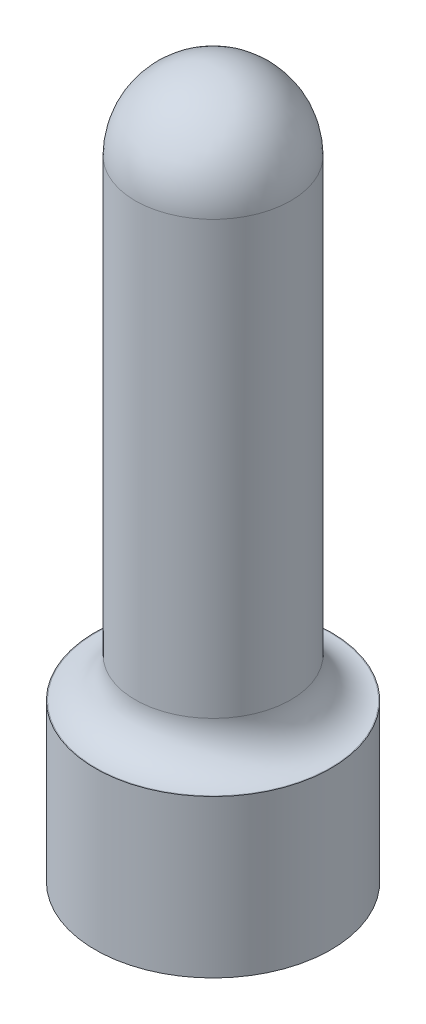
SolidWorks part; units mm, degrees
ref_plane "Plano frontal" through (0, 0, 0) normal (0, 0, 1) x (1, 0, 0)
ref_plane "Plano superior" through (0, 0, 0) normal (0, 1, 0) x (1, 0, 0)
ref_plane "Plano direito" through (0, 0, 0) normal (1, 0, 0) x (0, 0, -1)
sketch "Esboço1" plane through (0, 0, 0) normal (0, 1, 0) x (1, 0, 0)
  circle A0 centre (0, 0) radius 9.9
  dimension "D1" = 19.8
extrude "Ressalto-extrusão1" add sketch "Esboço1" along normal blind 80
sketch "Esboço3" plane through (0, 0, 0) normal (0, 0, 1) x (1, 0, 0)
  line L0 (-9.9, 80) -> (9.9, 80)
  arc A0 (-9.9, 80) -> (9.9, 80) centre (0, 80) cw
revolve "Revolução1" add sketch "Esboço3" angle 360 about L0
sketch "Esboço4" plane through (0, 0, 0) normal (0, -1, 0) x (1, 0, 0)
  circle A0 centre (0, 0) radius 15
  dimension "D1" = 30
extrude "Ressalto-extrusão2" add sketch "Esboço4" against normal blind 20
fillet "Filete3" radius 5 1 edges at (0, 20, -9.9)
